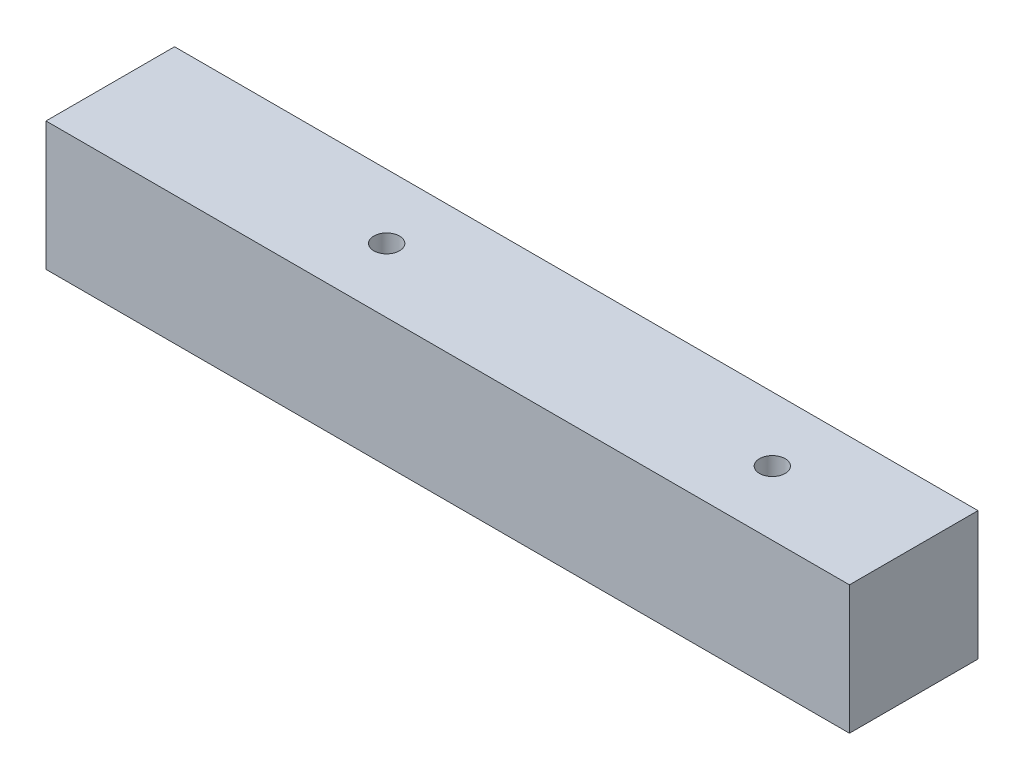
SolidWorks part; units mm, degrees
ref_plane "前视基准面" through (0, 0, 0) normal (0, 0, 1) x (1, 0, 0)
ref_plane "上视基准面" through (0, 0, 0) normal (0, 1, 0) x (1, 0, 0)
ref_plane "右视基准面" through (0, 0, 0) normal (1, 0, 0) x (0, 0, -1)
sketch "草图1" plane through (0, 0, 0) normal (0, 1, 0) x (1, 0, 0)
  line L1 (0, 0) -> (125, 0)
  line L2 (0, 0) -> (0, 20)
  line L3 (0, 20) -> (125, 20)
  line L4 (125, 0) -> (125, 20)
  dimension "D1" = 125
  dimension "D2" = 20
extrude "凸台-拉伸1" add sketch "草图1" along normal blind 20
hole_wizard "Ø4.0 (4) 直径孔1" positions "草图3" profile "草图2" hole size "Ø4.0" standard "GB" end condition through all
sketch "草图3" plane through (0, 20, 0) normal (0, 1, 0) x (1, 0, 0)
  line L1 (125, 0) -> (125, 20) construction
  line L2 (0, 0) -> (125, 0) construction
  point P0 (103, 10)
  point P2 (43, 10)
  dimension "D1" = 22
  dimension "D2" = 60
  dimension "D3" = 10
sketch "草图2" plane through (103, 20, -10) normal (1, 0, 0) x (0, 0, 1)
  line L0 (0, 0) -> (0, 20)
  line L1 (0, 20) -> (2, 20)
  line L2 (2, 20) -> (2, 0)
  line L5 (2, 0) -> (0, 0)
  line L11 (0, -6.35) -> (0, 107.95) construction
  dimension "通孔孔直径" = 4
  dimension "通孔孔深度" = 20
